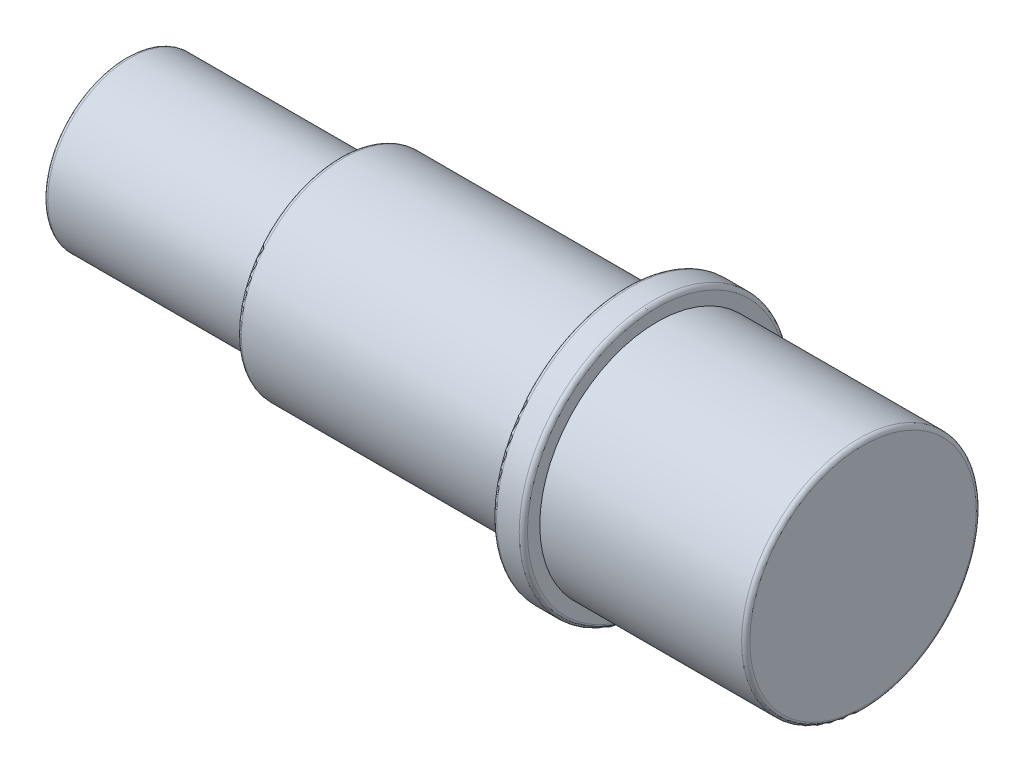
SolidWorks part; units mm, degrees
material "AISI 304"
ref_plane "Спереди" through (0, 0, 0) normal (0, 0, 1) x (1, 0, 0)
ref_plane "Сверху" through (0, 0, 0) normal (0, 1, 0) x (1, 0, 0)
ref_plane "Справа" through (0, 0, 0) normal (1, 0, 0) x (0, 0, -1)
sketch "Эскиз1" plane through (0, 0, 0) normal (0, 0, 1) x (1, 0, 0)
  line L0 (0, 0) -> (179.9726, 0) construction
  line L1 (0, 0) -> (0, 20)
  line L2 (0, 20) -> (52, 20)
  line L3 (52, 20) -> (52, 25)
  line L4 (52, 25) -> (121.5, 25)
  line L5 (121.5, 25) -> (121.5, 32.5)
  line L6 (121.5, 32.5) -> (129, 32.5)
  line L7 (129, 32.5) -> (129, 28.5)
  line L8 (129, 28.5) -> (179, 28.5)
  line L9 (179, 28.5) -> (179, 0)
  line L10 (179, 0) -> (0, 0)
  point P3 (125.25, 32.5)
  dimension "D1" = 57
  dimension "D2" = 50
  dimension "D3" = 7.5
  dimension "D4" = 40
  dimension "D5" = 50
  dimension "D6" = 65
  dimension "D7" = 179
  dimension "D8" = 127
revolve "Повернуть1" add sketch "Эскиз1" angle 360 about L0
hole_wizard "Отверстие обработанное метчиком M81" positions "Эскиз2" profile "Эскиз3" tap size "M8" standard "DIN"
sketch "Эскиз2" plane through (0, 0, 0) normal (-1, 0, 0) x (0, 0, 1)
  point P0 (0, 0)
sketch "Эскиз3" plane through (0, 0, 0) normal (0, 1, 0) x (0, 0, 1)
  line L0 (0, 0) -> (0, 24.2929)
  line L1 (0, 24.2929) -> (3.4, 22.25)
  line L2 (3.4, 22.25) -> (3.4, 0)
  line L5 (3.4, 0) -> (0, 0)
  line L10 (0, 24.2929) -> (-3.4, 22.25) construction
  line L11 (0, -6.35) -> (0, 107.95) construction
  dimension "Диаметр сверла" = 6.8
  dimension "Глубина сверла" = 22.25
  dimension "Угол заточки сверла" = 118
cosmetic thread "Отверстие резьбы1" parameters "D1"=16, "D2"=8
fillet "Скругление1" radius 1 5 edges at (179, 0, 28.5) (129, 0, 32.5) (121.5, 0, 32.5) (52, 0, 25) (0, 0, 20)
